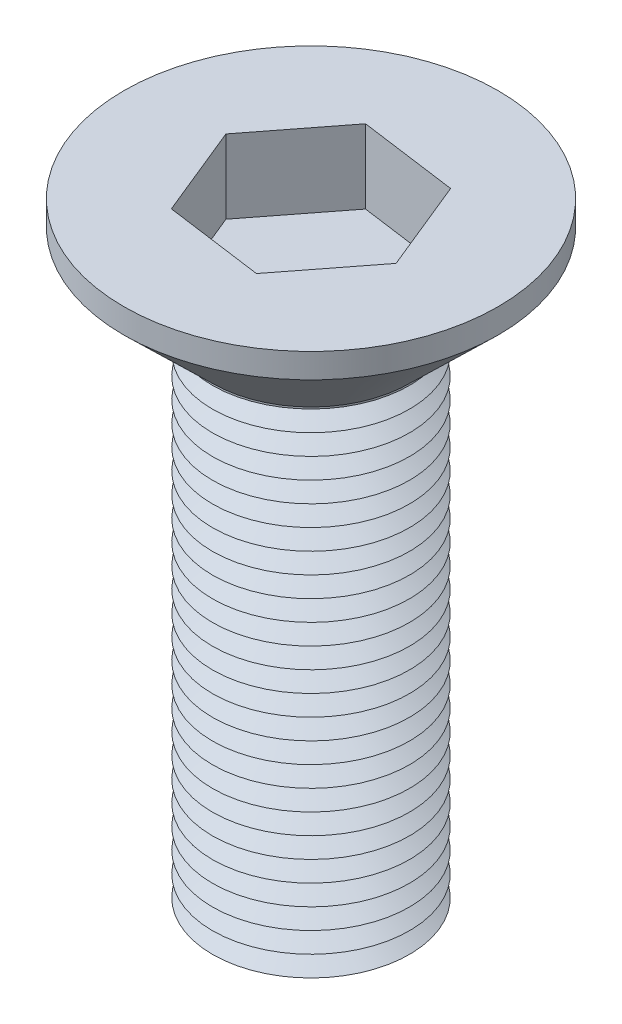
SolidWorks part; units mm, degrees
ref_plane "前视基准面" through (0, 0, 0) normal (0, 0, 1) x (1, 0, 0)
ref_plane "上视基准面" through (0, 0, 0) normal (0, 1, 0) x (1, 0, 0)
ref_plane "右视基准面" through (0, 0, 0) normal (1, 0, 0) x (0, 0, -1)
sketch "草图1" plane through (0, 0, 0) normal (0, 0, 1) x (1, 0, 0)
  line B0 (7.6, 25) -> (0, 25)
  line B1 (0, 25) -> (0, 0)
  line B2 (4, 20.5) -> (4, 20.4286)
  line B3 (3.3, 0) -> (4, 0.4169)
  line B4 (7.6, 24) -> (7.6, 25)
  line B5 (4, 20.5) -> (7.6, 24)
  line B6 (3.3, 0) -> (0, 0)
  line B7 (3.3, 0.8338) -> (4, 0.4169)
  line B8 (3.3, 0.8338) -> (4, 1.2507)
  line B9 (3.3, 1.6676) -> (4, 1.2507)
  line B10 (3.3, 1.6676) -> (4, 2.0846)
  line B11 (3.3, 2.5015) -> (4, 2.0846)
  line B12 (3.3, 2.5015) -> (4, 2.9184)
  line B13 (3.3, 3.3353) -> (4, 2.9184)
  line B14 (3.3, 3.3353) -> (4, 3.7522)
  line B15 (3.3, 4.1691) -> (4, 3.7522)
  line B16 (3.3, 4.1691) -> (4, 4.586)
  line B17 (3.3, 5.0029) -> (4, 4.586)
  line B18 (3.3, 5.0029) -> (4, 5.4198)
  line B19 (3.3, 5.8368) -> (4, 5.4198)
  line B20 (3.3, 5.8368) -> (4, 6.2537)
  line B21 (3.3, 6.6706) -> (4, 6.2537)
  line B22 (3.3, 6.6706) -> (4, 7.0875)
  line B23 (3.3, 7.5044) -> (4, 7.0875)
  line B24 (3.3, 7.5044) -> (4, 7.9213)
  line B25 (3.3, 8.3382) -> (4, 7.9213)
  line B26 (3.3, 8.3382) -> (4, 8.7551)
  line B27 (3.3, 9.172) -> (4, 8.7551)
  line B28 (3.3, 9.172) -> (4, 9.5889)
  line B29 (3.3, 10.0059) -> (4, 9.5889)
  line B30 (3.3, 10.0059) -> (4, 10.4228)
  line B31 (3.3, 10.8397) -> (4, 10.4228)
  line B32 (3.3, 10.8397) -> (4, 11.2566)
  line B33 (3.3, 11.6735) -> (4, 11.2566)
  line B34 (3.3, 11.6735) -> (4, 12.0904)
  line B35 (3.3, 12.5073) -> (4, 12.0904)
  line B36 (3.3, 12.5073) -> (4, 12.9242)
  line B37 (3.3, 13.3411) -> (4, 12.9242)
  line B38 (3.3, 13.3411) -> (4, 13.7581)
  line B39 (3.3, 14.175) -> (4, 13.7581)
  line B40 (3.3, 14.175) -> (4, 14.5919)
  line B41 (3.3, 15.0088) -> (4, 14.5919)
  line B42 (3.3, 15.0088) -> (4, 15.4257)
  line B43 (3.3, 15.8426) -> (4, 15.4257)
  line B44 (3.3, 15.8426) -> (4, 16.2595)
  line B45 (3.3, 16.6764) -> (4, 16.2595)
  line B46 (3.3, 17.5103) -> (4, 17.0933)
  line B47 (3.3, 17.5103) -> (4, 17.9272)
  line B48 (3.3, 18.3441) -> (4, 17.9272)
  line B49 (3.3, 18.3441) -> (4, 18.761)
  line B50 (3.3, 19.1779) -> (4, 18.761)
  line B51 (3.3, 20.0117) -> (4, 19.5948)
  line B52 (3.3, 20.0117) -> (4, 20.4286)
  line B53 (3.3, 19.1779) -> (4, 19.5948)
  line B54 (3.3, 16.6764) -> (4, 17.0933)
sketch_block_instance "A$C2E1A71BF-1"
sketch_block "A$C2E1A71BF"
revolve "旋转1" add sketch "草图1" angle 360 about L1
sketch "草图3" plane through (0, 25, 0) normal (0, 1, 0) x (1, 0, 0)
  line L1 (4.004, -0.5491) -> (2.4775, 3.193)
  line L2 (2.4775, 3.193) -> (-1.5265, 3.7421)
  line L3 (-1.5265, 3.7421) -> (-4.004, 0.5491)
  line L4 (-4.004, 0.5491) -> (-2.4775, -3.193)
  line L5 (-2.4775, -3.193) -> (1.5265, -3.7421)
  line L6 (1.5265, -3.7421) -> (4.004, -0.5491)
  circle A0 centre (0, 0) radius 3.5 construction
extrude "切除-拉伸1" cut sketch "草图3" against normal blind 3
